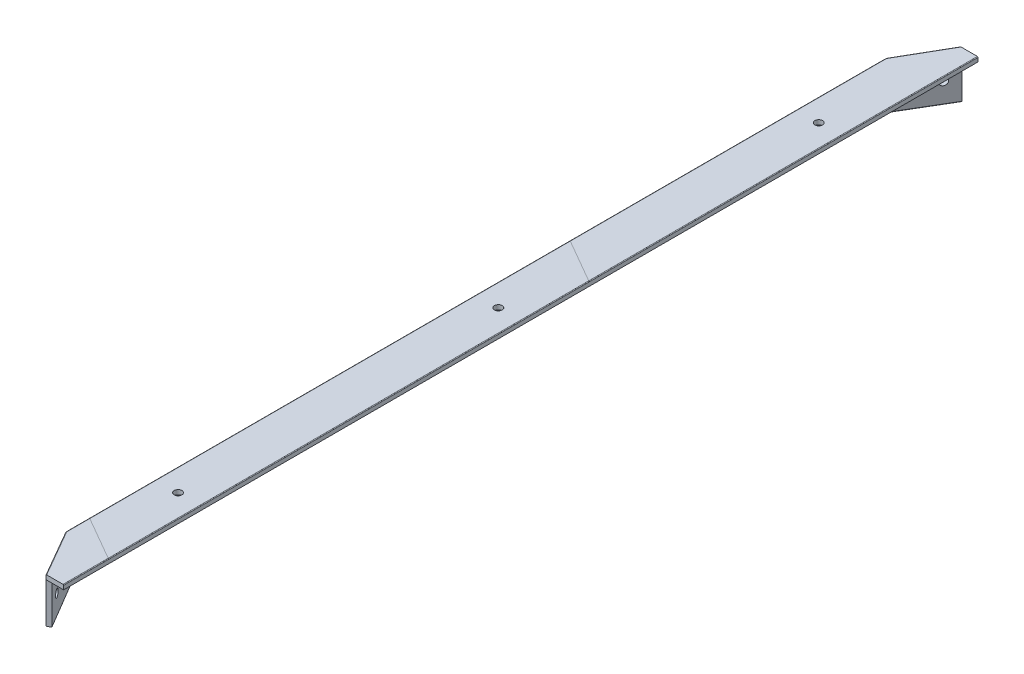
SolidWorks part; units mm, degrees
material "1.0116 (S235J2G3)"
ref_plane "Front Plane" through (0, 0, 0) normal (0, 0, 1) x (1, 0, 0)
ref_plane "Top Plane" through (0, 0, 0) normal (0, 1, 0) x (1, 0, 0)
ref_plane "Right Plane" through (0, 0, 0) normal (1, 0, 0) x (0, 0, -1)
sketch "Sketch1" plane through (0, 0, 0) normal (0, 0, 1) x (1, 0, 0)
  line L6 (0, 0) -> (0, 70)
  line L7 (0, 70) -> (70, 70)
  line L8 (70, 70) -> (70, 63)
  line L9 (70, 63) -> (7, 63)
  line L10 (7, 63) -> (7, 0)
  line L11 (7, 0) -> (0, 0)
  dimension "D1" = 70
  dimension "D2" = 70
  dimension "D3" = 7
  dimension "D4" = 7
extrude "Boss-Extrude1" add sketch "Sketch1" along normal blind 640
sketch "Sketch21" plane through (0, 0, 0) normal (0, 0, -1) x (-1, 0, 0)
  line L0 (0, 70) -> (-70, 70) construction
  line L1 (-70, 70) -> (-70, 0) construction
  line L2 (-70, 0) -> (0, 0) construction
  line L3 (0, 0) -> (0, 69.2595) construction
sketch "Sketch22" plane through (0, 70, 0) normal (0, 1, 0) x (1, 0, 0)
  line L0 (70, 0) -> (0, 0) construction
  line L1 (0, -55) -> (0, 55) construction
  circle A0 centre (35, 0) radius 6
  circle A1 centre (35, 500) radius 6
  circle A2 centre (35, -500) radius 6
  dimension "D1" = 12
  dimension "D2" = 12
  dimension "D3" = 12
  dimension "D4" = 500
  dimension "D5" = 500
  dimension "D6" = 35
  dimension "D7" = 35
extrude "Cut-Extrude4" cut sketch "Sketch22" against normal blind 10
sketch "Sketch23" plane through (0, 0, 0) normal (0, 1, 0) x (1, 0, 0)
  line L0 (0, -640) -> (42.5, -713.6122)
  line L1 (42.5, -713.6122) -> (48.5622, -710.1122)
  line L2 (48.5622, -710.1122) -> (7, -640)
  line L3 (7, -640) -> (0, -640)
  line L4 (0, -55) -> (0, 55) construction
  dimension "D1" = 7
  dimension "D2" = 210
  dimension "D3" = 85
extrude "Boss-Extrude2" add sketch "Sketch23" along normal blind 63
sketch "Sketch25" plane through (0, 63, 0) normal (0, 1, 0) x (1, 0, 0)
  line L0 (70, -640) -> (0, -640)
  line L1 (70, -640) -> (70, 0) construction
  line L2 (7, -640) -> (70, -640) construction
  line L3 (0, -640) -> (42.5, -713.6122) construction
  line L4 (0, -640) -> (42.5, -713.6122)
  line L5 (42.5, -713.6122) -> (48.5622, -710.1122) construction
  line L6 (42.5, -713.6122) -> (70, -713.6122)
  line L7 (70, -713.6122) -> (70, -640)
extrude "Boss-Extrude3" add sketch "Sketch25" along normal blind 7
sketch "Sketch26" plane through (-275.5567, 0, 163.3488) normal (0.8602, 0, -0.5099) x (-0.5099, 0, -0.8602)
  line L0 (-635.6125, 0) -> (-554.1071, 0) construction
  line L1 (-635.6125, 63) -> (-635.6125, 0) construction
  line L2 (-554.1071, 0) -> (-554.1071, 63) construction
  circle A0 centre (-614.3625, 31.5) radius 6
  circle A1 centre (-575.3671, 31.5) radius 6
  dimension "D1" = 12
  dimension "D2" = 12
  dimension "D3" = 31.5
  dimension "D4" = 31.5
  dimension "D5" = 21.25
  dimension "D6" = 21.26
extrude "Cut-Extrude5" cut sketch "Sketch26" against normal blind 7
mirror "Mirror1" about plane through (0, 0, 0) normal (0, 0, 1) of bodies 114 116
fillet "Fillet1" radius 10 2 edges at (0, 35, 640) (0, 35, -640)
fillet "Fillet2" radius 10 2 edges at (7, 31.5, 640) (7, 31.5, -640)
sketch "Sketch27" plane through (0, 70, 0) normal (0, 1, 0) x (1, 0, 0)
  line L0 (0, -603.1976) -> (70, -643.6122)
  line L1 (0, -38.5) -> (0, 38.5) construction
  line L2 (70, -713.6122) -> (70, 713.6122) construction
  line L3 (70, -643.6122) -> (70, 106.3878)
  line L4 (70, 106.3878) -> (0, 146.8024)
  line L5 (0, 146.8024) -> (0, -603.1976)
  line L6 (42.5, -713.6122) -> (70, -713.6122) construction
  dimension "D1" = 60
  dimension "D2" = 60
  dimension "D3" = 70
  dimension "D4" = 750
split line "Split Line1"
fillet "Fillet3" radius 5 5 edges at (28.48, 63, 676.2351) (7.3558, 63, 639.9025) (28.48, 63, -676.2351) (7.3558, 63, -639.9025) (7, 63, 0)
fillet "Fillet5" radius 1 20 edges at (0, 70, 620.2591) (0, 0, 0) (70, 70, 678.6122) (21.9199, 0, -677.9663) (21.9199, 0, 677.9663) (0.3407, 0, 639.9087) (0.3407, 0, -639.9087) (21.9199, 70, -677.9663) (21.9199, 70, 677.9663) (0.3407, 70, 639.9087) (0.3407, 70, -639.9087) (7, 0, 0) (7.3558, 0, 639.9025) (7.3558, 0, -639.9025) (0, 70, 228.1976) (0, 70, -392.0614) (70, 70, 268.6122) (70, 70, -410) (28.48, 0, 676.2351) (28.48, 0, -676.2351)
